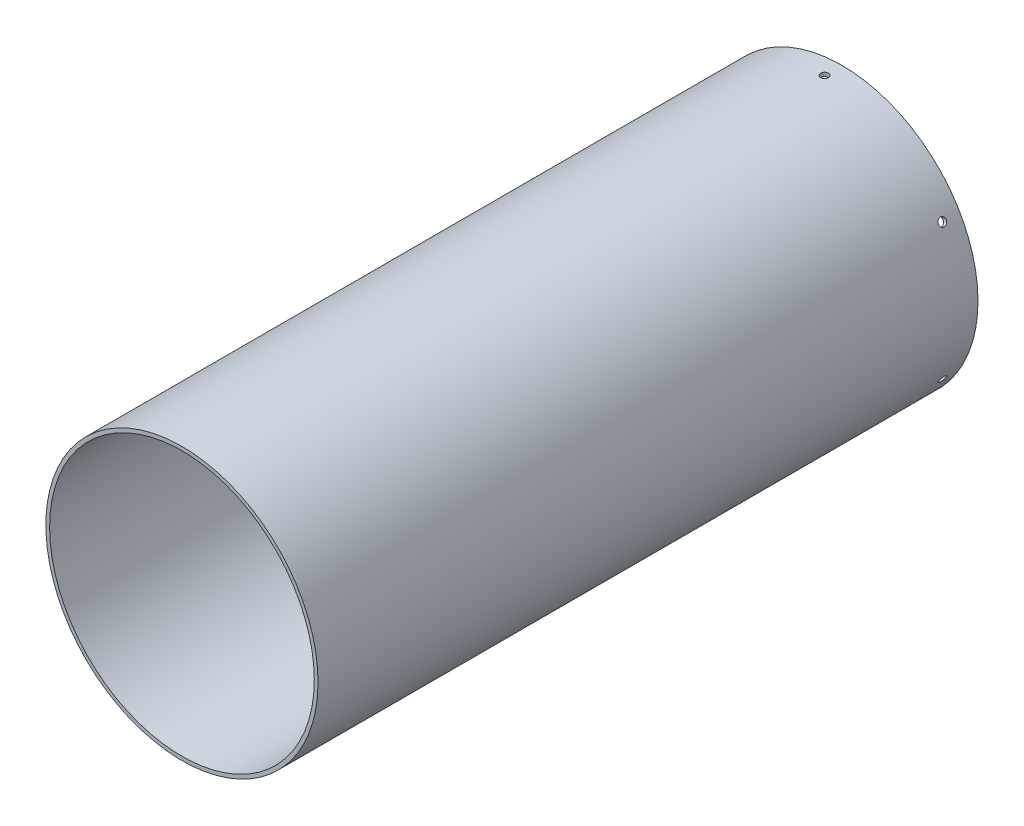
SolidWorks part; units mm, degrees
material "A-Glass Fiber"
ref_plane "Front Plane" through (0, 0, 0) normal (0, 0, 1) x (1, 0, 0)
ref_plane "Top Plane" through (0, 0, 0) normal (0, 1, 0) x (1, 0, 0)
ref_plane "Right Plane" through (0, 0, 0) normal (1, 0, 0) x (0, 0, -1)
sketch "Sketch1" plane through (0, 0, 0) normal (0, 0, 1) x (1, 0, 0)
  circle A0 centre (0, 0) radius 76.2
  circle A1 centre (0, 0) radius 78.359
  dimension "D1" = 156.718
  dimension "D2" = 152.4
extrude "Boss-Extrude1" add sketch "Sketch1" along normal blind 380
sketch "Sketch4" plane through (0, 0, 0) normal (0, 1, 0) x (1, 0, 0)
  line L0 (78.359, 0) -> (-78.359, 0) construction
  point P0 (0, -10)
  dimension "D1" = 10
hole_wizard "M4 Clearance Hole2" positions "Sketch4" profile "Sketch5" hole size "M4" standard "ANSI Metric"
sketch "Sketch5" plane through (0, 0, 10) normal (1, 0, 0) x (0, 0, -1)
  line L0 (0, 0) -> (0, 78.359)
  line L1 (0, 78.359) -> (2.25, 78.359)
  line L2 (2.25, 78.359) -> (2.25, 0)
  line L5 (2.25, 0) -> (0, 0)
  line L11 (0, -6.35) -> (0, 107.95) construction
  dimension "Thru Hole Dia." = 4.5
  dimension "Thru Hole Depth" = 78.359
pattern_circular "CirPattern2" count 6 over 360 about axis through (0, 0, 380) along (0, 0, -1) of "M4 Clearance Hole2"
